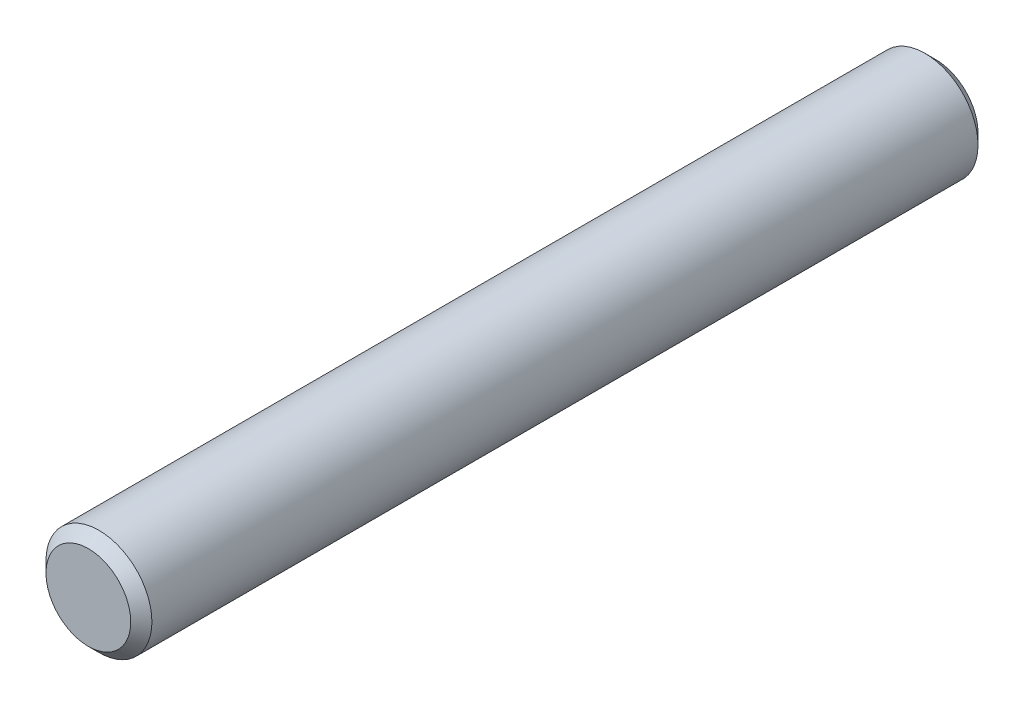
SolidWorks part; units mm, degrees
ref_plane "Front" through (0, 0, 0) normal (0, 0, 1) x (1, 0, 0)
ref_plane "Top" through (0, 0, 0) normal (0, 1, 0) x (1, 0, 0)
ref_plane "Right" through (0, 0, 0) normal (1, 0, 0) x (0, 0, -1)
sketch "Sketch1" plane through (0, 0, 0) normal (0, 0, 1) x (1, 0, 0)
  circle A0 centre (0, 0) radius 3.175 construction
  dimension "Diameter" = 6.35
sketch "Sketch2" plane through (0, 0, 0) normal (1, 0, 0) x (0, 0, -1)
  line L0 (-12.7, 0) -> (12.7, 0) construction
  line L1 (3.4925, 0) -> (-3.4925, 0) construction
  line L3 (12.7, 3.175) -> (12.7, -3.175) construction
  line L4 (-12.7, 3.175) -> (-12.7, -3.175) construction
  line L5 (-4.7625, 3.175) -> (-4.7625, -3.175) construction
  line L6 (4.7625, 3.175) -> (4.7625, -3.175) construction
  point P6 (0, 0)
  point P10 (12.7, 0)
  point P13 (-12.7, 0)
  point P16 (-4.7625, 0)
  point P19 (4.7625, 0)
  dimension "D1" = 6.35
  dimension "Length" = 25.4
  dimension "D2" = 7.9375
  dimension "D3" = 7.9375
sketch "Sketch3" plane through (0, 0, 0) normal (0, 0, 1) x (1, 0, 0)
  line L0 (0, 3.175) -> (0, -3.175) construction
  circle A0 centre (0, 0) radius 3.175
  dimension "D1" = 6.35
extrude "Boss-Extrude1" add sketch "Sketch3" along normal mid plane 50.8
chamfer "Chamfer1" distance 0.635 angle 45 2 edges at (3.175, 0, -25.4) (3.175, 0, 25.4)
equation "\"D1@Sketch2\" = \"Diameter@Sketch1\""
equation "\"D1@Sketch3\" = \"Diameter@Sketch1\""
equation "\"D1@Boss-Extrude1\"=2in"
equation "\"D1@Chamfer1\" = \"Diameter@Sketch1\" * .1"
equation "\"D2@Sketch2\"=\"Diameter@Sketch1\"*1.25"
equation "\"D3@Sketch2\"=\"D2@Sketch2\""
